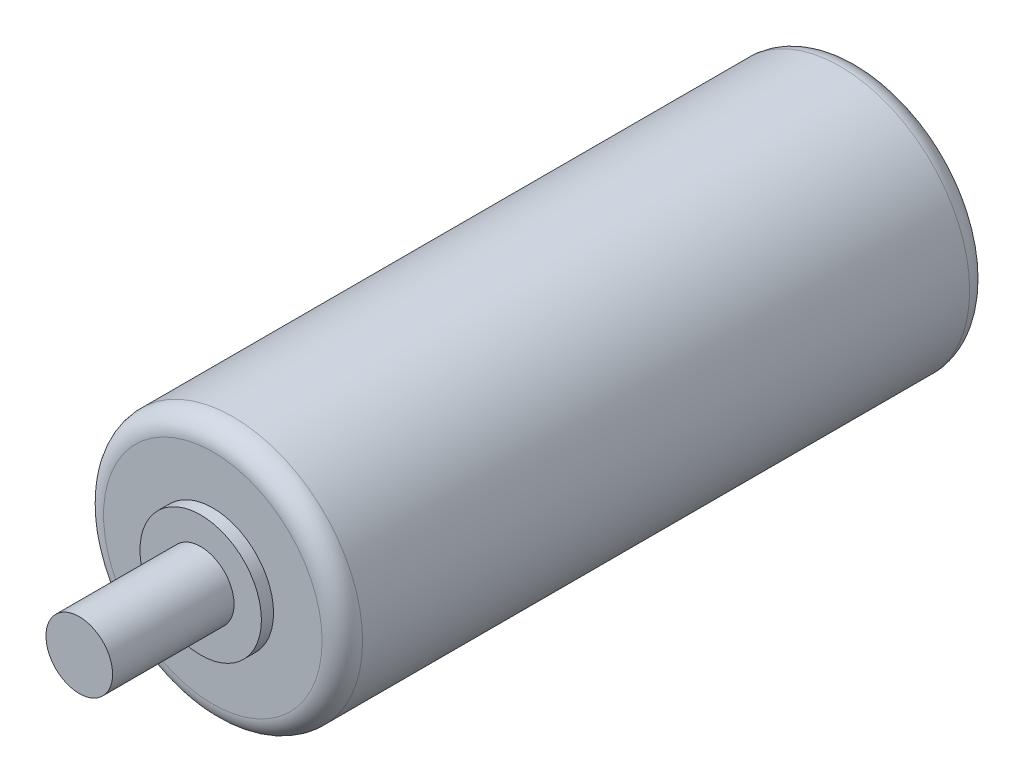
SolidWorks part; units mm, degrees
ref_plane "Alzado" through (0, 0, 0) normal (0, 0, 1) x (1, 0, 0)
ref_plane "Planta" through (0, 0, 0) normal (0, 1, 0) x (1, 0, 0)
ref_plane "Vista lateral" through (0, 0, 0) normal (1, 0, 0) x (0, 0, -1)
sketch "Croquis1" plane through (0, 0, 0) normal (0, 0, 1) x (1, 0, 0)
  circle A0 centre (0, 0) radius 32
  dimension "D1" = 64
extrude "Saliente-Extruir1" add sketch "Croquis1" along normal mid plane 160
fillet "Redondeo1" radius 5 2 edges at (32, 0, -80) (32, 0, 80)
sketch "Croquis2" plane through (0, 0, 80) normal (0, 0, 1) x (1, 0, 0)
  circle A0 centre (0, 0) radius 15
  dimension "D1" = 30
extrude "Saliente-Extruir2" add sketch "Croquis2" along normal blind 3
sketch "Croquis3" plane through (0, 0, -80) normal (0, 0, -1) x (-1, 0, 0)
  circle A0 centre (0, 0) radius 17.75
  dimension "D1" = 35.5
extrude "Saliente-Extruir3" add sketch "Croquis3" along normal blind 6
sketch "Croquis4" plane through (0, 0, 83) normal (0, 0, 1) x (1, 0, 0)
  circle A0 centre (0, 0) radius 8.2365
extrude "Saliente-Extruir4" add sketch "Croquis4" along normal blind 30
sketch "Croquis5" plane through (0, 0, -86) normal (0, 0, -1) x (-1, 0, 0)
  line L0 (0, 10.0318) -> (0, -9.6428) construction
  line L1 (-5.5, -8.5) -> (5.5, -8.5)
  line L3 (-5.5, 8.5) -> (5.5, 8.5)
  line L5 (-5.5, -8.5) -> (5.5, 8.5) construction
  line L6 (-5.5, 8.5) -> (5.5, -8.5) construction
  arc A0 (-5.5, -8.5) -> (-5.5, 8.5) centre (0.5546, 0) cw
  arc A1 (5.5, -8.5) -> (5.5, 8.5) centre (-0.5546, 0) ccw
  circle A2 centre (0, 0) radius 3.5
  point P0 (0, 0)
  dimension "D3" = 7
  dimension "D1" = 11
  dimension "D2" = 17
extrude "Saliente-Extruir5" add sketch "Croquis5" along normal blind 5
sketch "Croquis6" plane through (0, 0, -91) normal (0, 0, -1) x (-1, 0, 0)
  line L2 (10.8305, -10.0543) -> (-10.8305, -10.0543)
  line L3 (10.8305, -10.0543) -> (10.8305, 10.0543)
  line L4 (10.8305, 10.0543) -> (-10.8305, 10.0543)
  line L5 (-10.8305, -10.0543) -> (-10.8305, 10.0543)
  line L6 (10.8305, -10.0543) -> (-10.8305, 10.0543) construction
  line L7 (10.8305, 10.0543) -> (-10.8305, -10.0543) construction
  point P4 (0, 0)
extrude "Cortar-Extruir2" cut sketch "Croquis6" against normal up to surface (5 mm away) up to face at (0, 0, -86)
sketch "Croquis7" plane through (0, 0, -86) normal (0, 0, -1) x (-1, 0, 0)
  line L0 (-9.3808, 0) -> (9.6293, 0) construction
  line L2 (5.5, 8.5) -> (5.5, -8.5)
  line L4 (-5.5, 8.5) -> (-5.5, -8.5)
  line L5 (5.5, 8.5) -> (-5.5, -8.5) construction
  line L6 (5.5, -8.5) -> (-5.5, 8.5) construction
  arc A0 (-5.5, -8.5) -> (5.5, -8.5) centre (0, -3) ccw
  arc A1 (-5.5, 8.5) -> (5.5, 8.5) centre (0, 3) cw
  point P0 (0, 0)
  dimension "D1" = 11
  dimension "D2" = 17
extrude "Cortar-Extruir3" cut sketch "Croquis7" against normal blind 30
